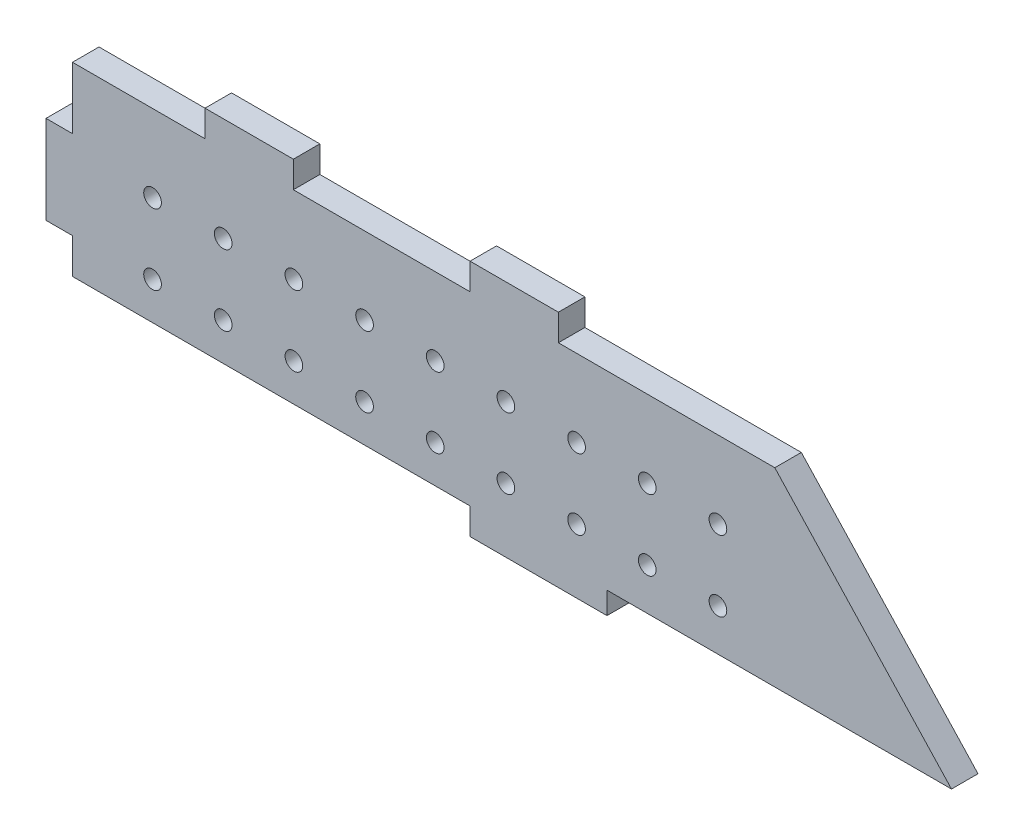
SolidWorks part; units mm, degrees
ref_plane "Plan de face" through (0, 0, 0) normal (0, 0, 1) x (1, 0, 0)
ref_plane "Plan de dessus" through (0, 0, 0) normal (0, 1, 0) x (1, 0, 0)
ref_plane "Plan de droite" through (0, 0, 0) normal (1, 0, 0) x (0, 0, -1)
sketch "Esquisse1" plane through (0, 0, 0) normal (0, 0, 1) x (1, 0, 0)
  line L1 (0, 0) -> (-199, 0)
  line L2 (0, 0) -> (0, 48)
  line L3 (0, 48) -> (-199, 48)
  line L4 (-199, 0) -> (-199, 48)
  dimension "D1" = 48
  dimension "D2" = 199
extrude "Boss.-Extru.1" add sketch "Esquisse1" along normal blind 6
sketch "Esquisse2" plane through (0, 48, 0) normal (0, 1, 0) x (1, 0, 0)
  line L0 (0, -6) -> (-199, -6) construction
  line L1 (-89, -6) -> (-109, -6)
  line L2 (-89, -6) -> (-89, 0)
  line L3 (-89, 0) -> (-109, 0)
  line L4 (-109, -6) -> (-109, 0)
  line L5 (0, 0) -> (-199, 0) construction
  line L6 (-199, -6) -> (-199, 0) construction
  line L7 (-149, -6) -> (-169, -6)
  line L8 (-149, -6) -> (-149, 0)
  line L9 (-149, 0) -> (-169, 0)
  line L10 (-169, -6) -> (-169, 0)
  dimension "D1" = 20
  dimension "D2" = 20
  dimension "D3" = 40
  dimension "D4" = 30
extrude "Boss.-Extru.2" add sketch "Esquisse2" along normal blind 6
sketch "Esquisse3" plane through (-199, 0, 0) normal (-1, 0, 0) x (0, 0, 1)
  line L1 (6, 48) -> (6, 0) construction
  line L2 (6, 34) -> (0, 34)
  line L3 (6, 34) -> (6, 14)
  line L4 (6, 14) -> (0, 14)
  line L6 (0, 34) -> (0, 14)
  line L7 (0, 48) -> (0, 0) construction
  line L8 (6, 48) -> (0, 48) construction
  dimension "D1" = 20
  dimension "D2" = 14
extrude "Boss.-Extru.3" add sketch "Esquisse3" along normal blind 6
sketch "Esquisse4" plane through (0, 0, 6) normal (0, 0, 1) x (1, 0, 0)
  line L1 (0, 0) -> (-78, 0)
  line L2 (0, 0) -> (0, 5)
  line L3 (0, 5) -> (-78, 5)
  line L4 (-78, 0) -> (-78, 5)
  dimension "D1" = 5
  dimension "D2" = 78
extrude "Enlèv. mat.-Extru.1" cut sketch "Esquisse4" against normal through all
sketch "Esquisse5" plane through (0, 0, 6) normal (0, 0, 1) x (1, 0, 0)
  line L0 (0, 48) -> (-40, 48)
  line L1 (0, 48) -> (-89, 48) construction
  line L2 (-40, 48) -> (0, 5)
  line L3 (0, 5) -> (0, 48)
  dimension "D1" = 159
extrude "Enlèv. mat.-Extru.2" cut sketch "Esquisse5" against normal through all
sketch "Esquisse6" plane through (0, 0, 6) normal (0, 0, 1) x (1, 0, 0)
  line L0 (-199, 0) -> (-78, 0) construction
  line L1 (-199, 14) -> (-199, 0) construction
  line L2 (-199, 48) -> (-199, 34) construction
  line L3 (-148.88, 14.5) -> (-164.88, 14.5) construction
  circle A0 centre (-148.88, 14.5) radius 1.005
  circle A1 centre (-148.88, 30.5) radius 1.005
  circle A2 centre (-132.88, 14.5) radius 1.005
  circle A3 centre (-132.88, 30.5) radius 1.005
  circle A4 centre (-116.88, 14.5) radius 1.005
  circle A5 centre (-116.88, 30.5) radius 1.005
  circle A6 centre (-100.88, 14.5) radius 1.005
  circle A7 centre (-100.88, 30.5) radius 1.005
  circle A8 centre (-84.88, 14.5) radius 1.005
  circle A9 centre (-84.88, 30.5) radius 1.005
  circle A10 centre (-68.88, 14.5) radius 1.005
  circle A11 centre (-68.88, 30.5) radius 1.005
  circle A12 centre (-52.88, 14.5) radius 1.005
  circle A13 centre (-52.88, 30.5) radius 1.005
  circle A14 centre (-164.88, 14.5) radius 1.005
  circle A15 centre (-164.88, 30.5) radius 1.005
  circle A16 centre (-180.88, 14.5) radius 1.005
  circle A17 centre (-180.88, 30.5) radius 1.005
  dimension "D1" = 2.01
  dimension "D2" = 2.01
  dimension "D3" = 2.01
  dimension "D4" = 2.01
  dimension "D12" = 50.12
  dimension "D16" = 14.5
  dimension "D17" = 14.5
  dimension "D18" = 16
  dimension "D5" = 16
  dimension "D6" = 16
  dimension "D7" = 16
  dimension "D8" = 16
  dimension "D9" = 14.5
  dimension "D10" = 50.12
  dimension "D11" = 14.5
  dimension "D15" = 16
  dimension "D13" = 6
  dimension "D14" = 3
extrude "Enlèv. mat.-Extru.3" cut sketch "Esquisse6" against normal through all
sketch "Esquisse7" plane through (0, 0, 6) normal (0, 0, 1) x (1, 0, 0)
  line L0 (-52.88, 14.5) -> (-68.88, 14.5) construction
  line L1 (-199, 0) -> (-78, 0) construction
  circle A0 centre (-52.88, 14.5) radius 2
  circle A1 centre (-52.88, 30.5) radius 2
  circle A2 centre (-68.88, 14.5) radius 2
  circle A3 centre (-68.88, 30.5) radius 2
  circle A4 centre (-84.88, 14.5) radius 2
  circle A5 centre (-84.88, 30.5) radius 2
  circle A6 centre (-100.88, 14.5) radius 2
  circle A7 centre (-100.88, 30.5) radius 2
  circle A8 centre (-116.88, 14.5) radius 2
  circle A9 centre (-116.88, 30.5) radius 2
  circle A10 centre (-132.88, 14.5) radius 2
  circle A11 centre (-132.88, 30.5) radius 2
  circle A12 centre (-148.88, 14.5) radius 2
  circle A13 centre (-148.88, 30.5) radius 2
  circle A14 centre (-164.88, 14.5) radius 2
  circle A15 centre (-164.88, 30.5) radius 2
  circle A16 centre (-180.88, 14.5) radius 2
  circle A17 centre (-180.88, 30.5) radius 2
  dimension "D1" = 4
  dimension "D2" = 4
  dimension "D5" = 14.5
  dimension "D4" = 16
  dimension "D3" = 9
extrude "Enlèv. mat.-Extru.4" cut sketch "Esquisse7" against normal blind 3
sketch "Esquisse8" plane through (0, 0, 0) normal (0, 0, -1) x (-1, 0, 0)
  line L1 (199, 0) -> (109, 0)
  line L2 (199, 0) -> (199, 6)
  line L3 (199, 6) -> (109, 6)
  line L4 (109, 0) -> (109, 6)
  dimension "D1" = 6
  dimension "D2" = 90
extrude "Enlèv. mat.-Extru.5" cut sketch "Esquisse8" against normal through all
